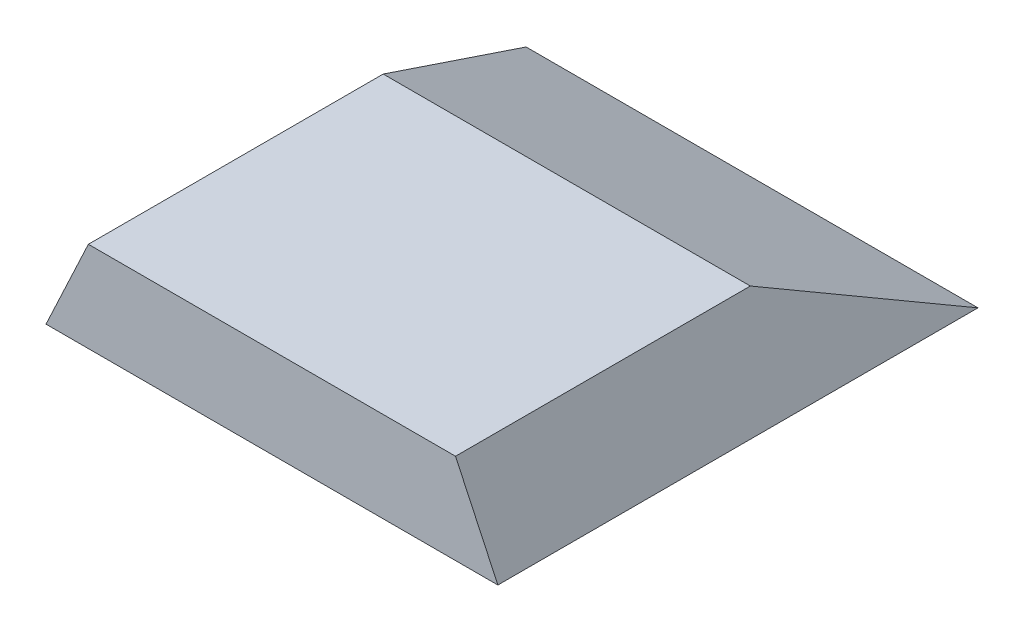
SolidWorks part; units mm, degrees
ref_plane "Front Plane" through (0, 0, 0) normal (0, 0, 1) x (1, 0, 0)
ref_plane "Top Plane" through (0, 0, 0) normal (0, 1, 0) x (1, 0, 0)
ref_plane "Right Plane" through (0, 0, 0) normal (1, 0, 0) x (0, 0, -1)
sketch "Sketch1" plane through (0, 0, 0) normal (0, 0, 1) x (1, 0, 0)
  line L0 (0, 14.8611) -> (0, -8.4611) construction
  line L9 (-6.5, 3.2) -> (-8, 0)
  line L10 (-8, 0) -> (8, 0)
  line L11 (8, 0) -> (6.5, 3.2)
  line L12 (6.5, 3.2) -> (-6.5, 3.2)
  point P4 (0, 0)
  point P9 (7.5682, 5.396)
  point P10 (0, 3.2)
  dimension "D1" = 13
  dimension "D2" = 16
  dimension "D3" = 3.2
extrude "Boss-Extrude1" add sketch "Sketch1" along normal blind 17
sketch "Sketch2" plane through (0, 0, 0) normal (1, 0, 0) x (0, 0, -1)
  line L0 (0, 0) -> (-6.561, 3.2)
  line L1 (-17, 3.2) -> (0, 3.2) construction
  line L2 (-17, 0) -> (0, 0) construction
  line L3 (-6.561, 3.2) -> (0, 3.2)
  line L4 (0, 3.2) -> (0, 0)
  dimension "D1" = 26
extrude "Cut-Extrude1" cut sketch "Sketch2" against normal through all both and the other way through all
